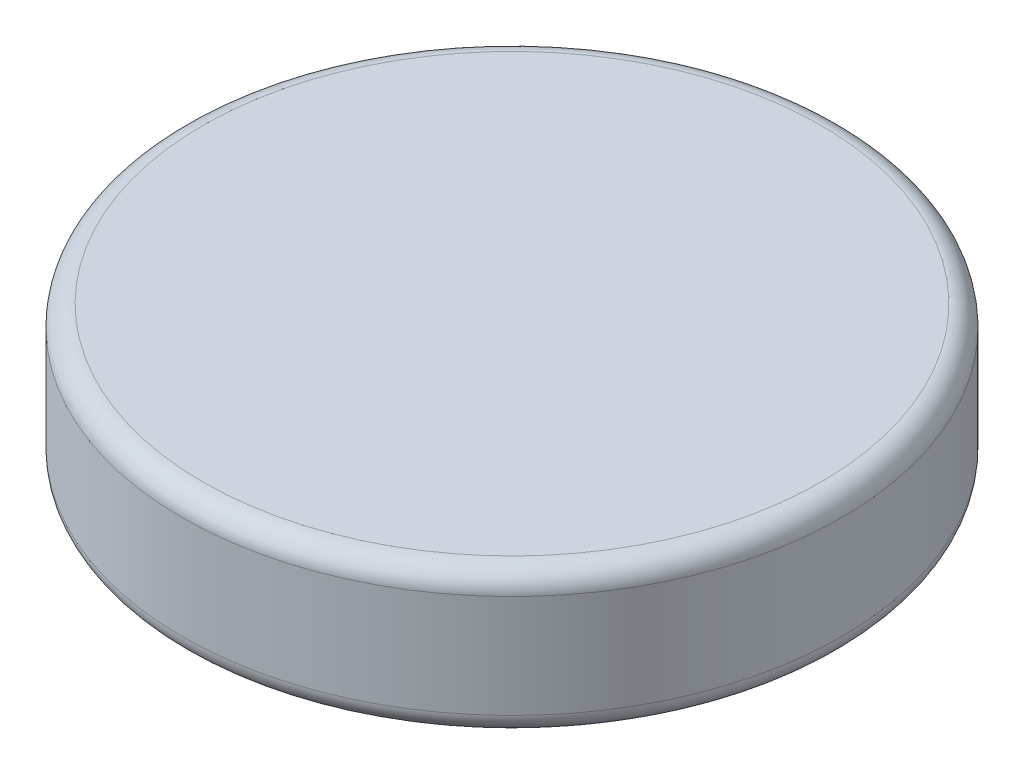
SolidWorks part; units mm, degrees
material "ABS"
ref_plane "Ebene vorne" through (0, 0, 0) normal (0, 0, 1) x (1, 0, 0)
ref_plane "Ebene oben" through (0, 0, 0) normal (0, 1, 0) x (1, 0, 0)
ref_plane "Ebene rechts" through (0, 0, 0) normal (1, 0, 0) x (0, 0, -1)
sketch "Skizze1" plane through (0, 0, 0) normal (0, 1, 0) x (1, 0, 0)
  circle A0 centre (0, 0) radius 16
  dimension "D1" = 32
extrude "Base" add sketch "Skizze1" along normal mid plane 7
fillet "Edge Rouding" radius 1 2 edges at (0, -3.5, 16) (0, 3.5, 16)
sketch "Axis" plane through (0, 0, 0) normal (0, 0, 1) x (1, 0, 0)
  line L0 (0, 3.5) -> (0, -3.5) construction
  line L1 (15, 3.5) -> (-15, 3.5) construction
  line L2 (-15, -3.5) -> (15, -3.5) construction
